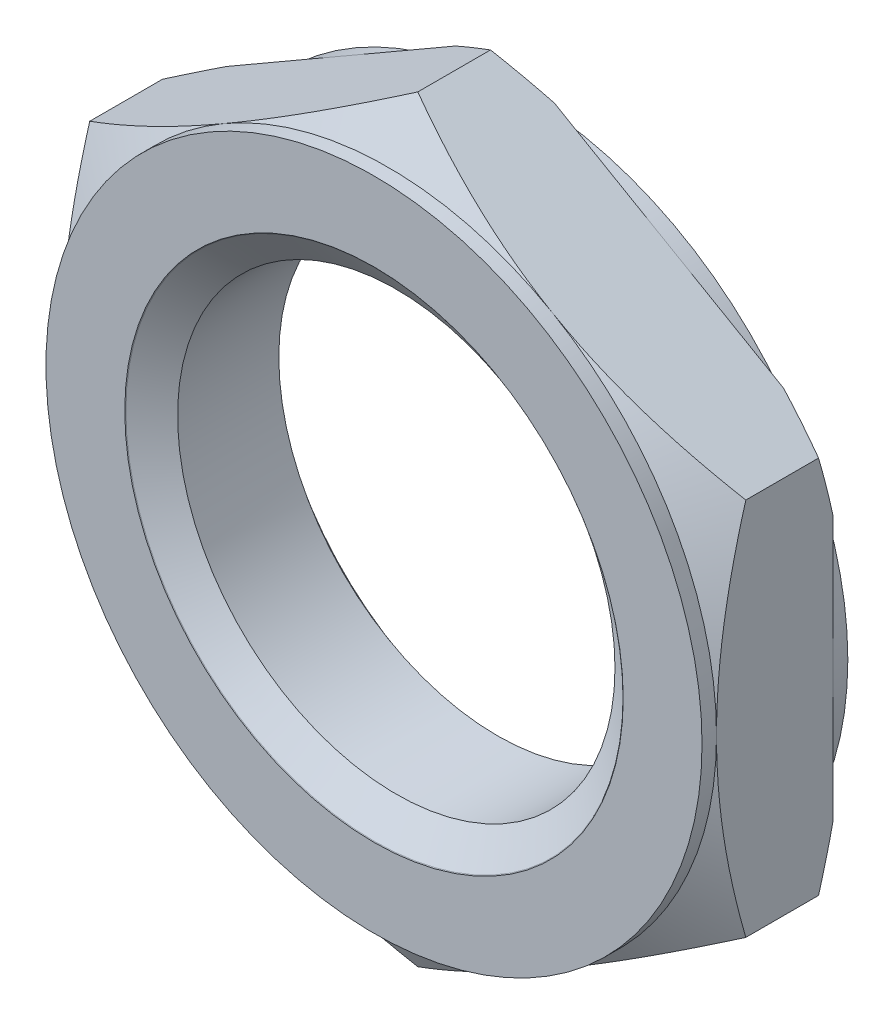
SolidWorks part; units mm, degrees
ref_plane "Plane1" through (0, 0, 0) normal (0, 0, 1) x (1, 0, 0)
ref_plane "Plane2" through (0, 0, 0) normal (0, 1, 0) x (1, 0, 0)
ref_plane "Plane3" through (0, 0, 0) normal (1, 0, 0) x (0, 0, -1)
sketch "BaseNutSke" plane through (0, 0, 0) normal (0, 0, 1) x (1, 0, 0)
  line L6 (9, 5.1962) -> (9, -5.1962)
  line L7 (-9, 5.1962) -> (-9, -5.1962)
  line L8 (9, 5.1962) -> (0, 10.3923)
  line L9 (0, 10.3923) -> (-9, 5.1962)
  line L10 (-9, -5.1962) -> (0, -10.3923)
  line L11 (0, -10.3923) -> (9, -5.1962)
  circle A0 centre (0, 0) radius 5.25
  dimension "D4" = 9
  dimension "Tap_drill" = 10.5
  dimension "D1" = 120
  dimension "D2" = 9
  dimension "D3" = 9
  dimension "Width_flats" = 18
extrude "BaseNut" add sketch "BaseNutSke" against normal blind 4
cosmetic thread "ThreadCosmetic" parameters "Thread_major"=13.675
sketch "Sketch4" plane through (0, 0, 0) normal (1, 0, 0) x (0, 0, -1)
  line L0 (4, 9) -> (3.5936, 9)
  line L1 (4, 9) -> (4, 20.3923)
  line L2 (3.5936, 20.3923) -> (4, 20.3923)
  line L3 (3.5936, 20.3923) -> (3.5936, 9)
  line L4 (0, 0) -> (34.925, 0) construction
  line L6 (4, 5.1962) -> (4, 10.3923) construction
  line L7 (0, 9) -> (-10, 9)
  line L8 (0, 5.1962) -> (0, 10.3923) construction
  line L9 (0.8038, 10.3923) -> (0.8038, 20.3923)
  line L10 (0.8038, 20.3923) -> (-10, 20.3923)
  line L11 (-10, 20.3923) -> (-10, 9)
  line L12 (0, 9) -> (0.8038, 10.3923)
  line L14 (0, 5.1962) -> (0, -5.1962) construction
  line L15 (4, 10.3923) -> (0, 10.3923) construction
  dimension "D1" = 9
  dimension "D2" = 30
  dimension "Bearing_ht" = 0.4064
  dimension "D3" = 10
  dimension "D4" = 10
revolve "Bearing-Face" cut sketch "Sketch4" angle 360 about L4
sketch "Sketch3" plane through (0, 0, 0) normal (1, 0, 0) x (0, 0, -1)
  line L0 (4, 9) -> (3.1962, 10.3923)
  line L1 (3.1962, 10.3923) -> (3.1962, 20.3923)
  line L2 (3.1962, 20.3923) -> (14, 20.3923)
  line L3 (14, 20.3923) -> (14, 9)
  line L4 (14, 9) -> (4, 9)
  line L5 (4, 5.1962) -> (4, 10.3923) construction
  line L6 (3.5936, 10.3923) -> (0.8038, 10.3923) construction
  line L7 (0, 0) -> (38.6776, 0) construction
  line L8 (4, 0) -> (0, 0) construction
  line L9 (2.1987, 10.3923) -> (2.1987, 44.222) construction
  line L10 (1.2013, 20.3923) -> (-9.6026, 20.3923)
  line L11 (-9.6026, 20.3923) -> (-9.6026, 9)
  line L12 (-9.6026, 9) -> (0.3974, 9)
  line L13 (0.3974, 9) -> (1.2013, 10.3923)
  line L14 (1.2013, 10.3923) -> (1.2013, 20.3923)
  line L16 (3.5936, 10.3923) -> (0.8038, 10.3923) construction
  dimension "D1" = 9
  dimension "D2" = 30
  dimension "D3" = 10
  dimension "D4" = 10
revolve "Double-Chamfer" cut sketch "Sketch3" angle 360 about L7
sketch "Sketch5" plane through (0, 0, 0) normal (1, 0, 0) x (0, 0, -1)
  line L0 (3.9746, 6.8375) -> (2.7519, 5.0913)
  line L1 (4.0254, 6.8375) -> (3.9746, 6.8375)
  line L2 (4.0254, 6.8375) -> (4.0254, 5.0913)
  line L3 (4.0254, 5.0913) -> (2.7519, 5.0913)
  line L6 (-0.0508, 6.8375) -> (0, 6.8375)
  line L7 (0, 6.8375) -> (1.2227, 5.0913)
  line L9 (1.2227, 5.0913) -> (-0.0508, 5.0913)
  line L10 (-0.0508, 5.0913) -> (-0.0508, 6.8375)
  line L11 (25.0375, 0) -> (38.388, 0) construction
  line L12 (4, 0) -> (0, 0) construction
  dimension "D1" = 35
  dimension "D2" = 0.0508
  dimension "Offset1" = 4.0254
  dimension "ThreadMajor" = 6.8375
  dimension "ChamferDepth" = 1.7463
  dimension "Offset2" = 4.0762
revolve "EndChamfer" cut sketch "Sketch5" angle 360 about L11
sketch "ThdSchSke" plane through (0, 0, 0) normal (0, 1, 0) x (1, 0, 0)
  line L0 (-6.8375, 0.0254) -> (-5.25, 1.137)
  line L1 (-5.25, 1.137) -> (-2.625, 1.137)
  line L2 (-2.625, 1.137) -> (-2.625, -1.0862)
  line L3 (-2.625, -1.0862) -> (-5.25, -1.0862)
  line L4 (-5.25, -1.0862) -> (-6.8375, 0.0254)
  line L5 (-3.175, 3.175) -> (3.175, 3.175) construction
  line L6 (0, 3.175) -> (0, -2.9874) construction
  line L7 (0, 2.863) -> (0, 1.1116) construction
  dimension "D1" = 0.0254
  dimension "VeeAngle" = 70
  dimension "SideAngle" = 55
  dimension "OverCut" = 5.25
  dimension "Tap_Drill" = 10.5
  dimension "Advance" = 3.175
  dimension "Thread_major" = 13.675
revolve "ThreadSchematic" cut sketch "ThdSchSke" angle 360 about L6
pattern_linear "ThdSchPat" [suppressed]
sketch "Sketch6" plane through (0, 0, 0) normal (0, 0, 1) x (1, 0, 0)
  circle A1 centre (0, 0) radius 6
  dimension "D1" = 12
extrude "Cut-Extrude1" cut sketch "Sketch6" against normal blind 10
equation "\"D2@BaseNutSke\" = \"Width_flats@BaseNutSke\" / 2"
equation "\"D3@BaseNutSke\" = \"Width_flats@BaseNutSke\" / 2"
equation "\"D1@Sketch3\" = \"Width_flats@BaseNutSke\" /2"
equation "\"D1@Sketch4\" = \"D2@BaseNutSke\""
equation "\"D4@BaseNutSke\" = \"D3@BaseNutSke\""
equation "\"Thread_major@ThdSchSke\" = \"Thread_major@ThreadCosmetic\""
equation "\"Tap_drill@ThdSchSke\" = \"Tap_drill@BaseNutSke\""
equation "\"Overcut@ThdSchSke\" = \"Tap_drill@ThdSchSke\" * 0.5"
equation "\"Num_threads@ThdSchPat\" = int(  ( \"Thickness@BaseNut\" - 0.0508 ) / \"Advance@ThdSchSke\" + 0.999 )  + 1"
equation "\"Advance@ThdSchPat\" = ( \"Thickness@BaseNut\" - 0.0508 ) /  (\"Num_threads@ThdSchPat\" - 1) 'relax it"
equation "' \"Num_threads@ThdSchPat\" = \"Num_threads@ThdSchPat\" - sgn( \"Num_threads@ThdSchPat\" - 1) '---chamfered tips only---"
equation "\"ThreadMajor@Sketch5\" = \"Thread_major@ThreadCosmetic\" * 0.5"
equation "\"ChamferDepth@Sketch5\" = (\"Thread_major@ThreadCosmetic\" - \"Tap_drill@BaseNutSke\") * 0.55"
equation "\"Offset1@Sketch5\" = \"Thickness@BaseNut\" + 0.0254"
equation "\"Offset2@Sketch5\" = \"Offset1@Sketch5\" + 0.0508"
